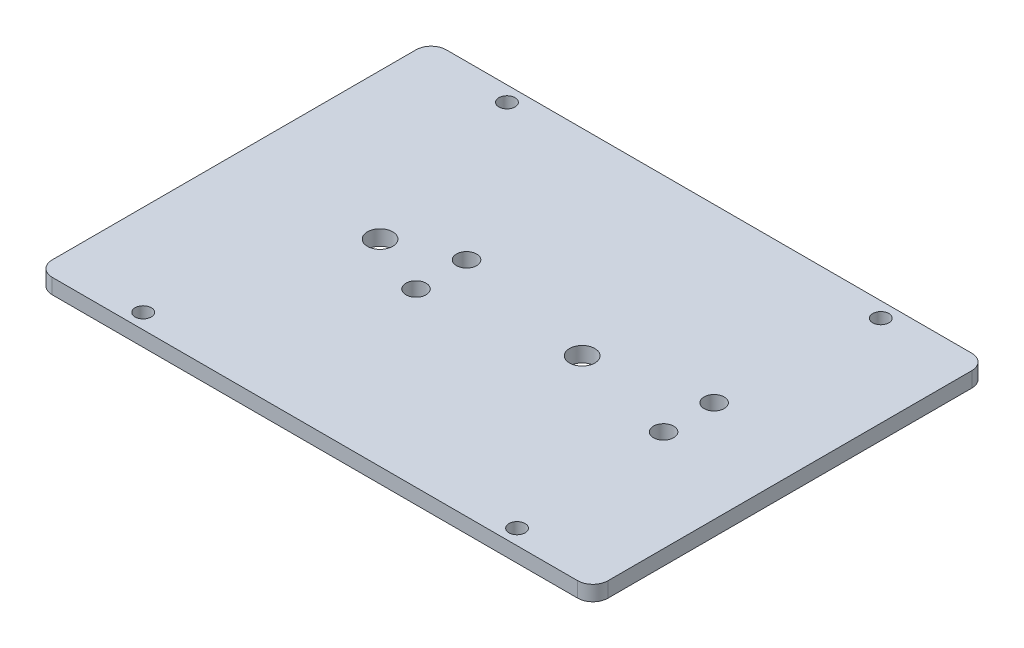
SolidWorks part; units mm, degrees
ref_plane "前视基准面" through (0, 0, 0) normal (0, 0, 1) x (1, 0, 0)
ref_plane "上视基准面" through (0, 0, 0) normal (0, 1, 0) x (1, 0, 0)
ref_plane "右视基准面" through (0, 0, 0) normal (1, 0, 0) x (0, 0, -1)
other "Configuration Table"
sketch "草图1" plane through (0, 0, 0) normal (0, 1, 0) x (1, 0, 0)
  line L0 (-37, -36) -> (37, -36) construction
  line L1 (-37, -36) -> (-37, 36) construction
  line L2 (-37, 36) -> (37, 36) construction
  line L3 (37, -36) -> (37, 36) construction
  line L4 (55, -39) -> (-55, -39)
  line L5 (55, -39) -> (55, 39)
  line L6 (55, 39) -> (-55, 39)
  line L7 (-55, -39) -> (-55, 39)
  line L8 (55, -39) -> (-55, 39) construction
  line L9 (55, 39) -> (-55, -39) construction
  circle A0 centre (-37, 36) radius 1.6
  circle A1 centre (37, 36) radius 1.6
  circle A2 centre (37, -36) radius 1.6
  circle A3 centre (-37, -36) radius 1.6
  point P4 (0, 0)
  point P5 (37, 0)
  point P6 (0, 36)
  point P7 (0, 0)
  dimension "D5" = 3.2
  dimension "D6" = 3.2
  dimension "D7" = 3.2
  dimension "D8" = 3.2
  dimension "D1" = 74
  dimension "D2" = 72
  dimension "D3" = 110
  dimension "D4" = 78
extrude "凸台-拉伸1" add sketch "草图1" along normal blind 3
fillet "圆角1" radius 3 4 edges at (-55, 1.5, -39) (-55, 1.5, 39) (55, 1.5, -39) (55, 1.5, 39)
sketch "草图2" plane through (0, 3, 0) normal (0, 1, 0) x (1, 0, 0)
  line L1 (0.2939, 0) -> (4.928, 0) construction
  circle A0 centre (-14, 5) radius 2
  circle A2 centre (35, 5) radius 2
  circle A3 centre (35, -5) radius 2
  circle A4 centre (-14, -5) radius 2
  dimension "D2" = 5
  dimension "D4" = 4
  dimension "D5" = 4
  dimension "D1" = 14
  dimension "D3" = 49
extrude "切除-拉伸1" cut sketch "草图2" against normal blind 10
sketch "草图3" plane through (0, 0, 0) normal (0, -1, 0) x (1, 0, 0)
  circle A0 centre (-26.1106, 0) radius 2.5
  circle A1 centre (13.8894, 0) radius 2.5
  dimension "D1" = 40
extrude "切除-拉伸2" cut sketch "草图3" against normal blind 10
